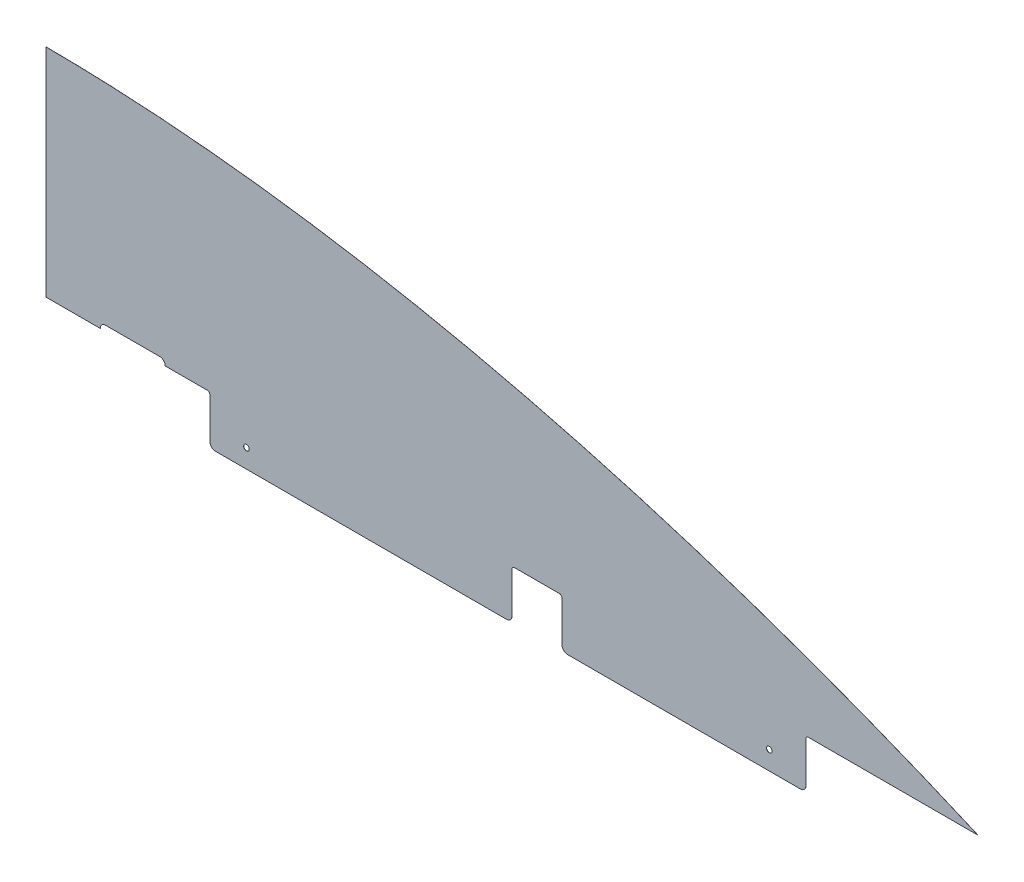
SolidWorks part; units mm, degrees
material "PC High Viscosity"
ref_plane "Front Plane" through (0, 0, 0) normal (0, 0, 1) x (1, 0, 0)
ref_plane "Top Plane" through (0, 0, 0) normal (0, 1, 0) x (1, 0, 0)
ref_plane "Right Plane" through (0, 0, 0) normal (1, 0, 0) x (0, 0, -1)
sketch "Sketch1" plane through (0, 0, 0) normal (0, 0, 1) x (1, 0, 0)
  line L0 (0, 254) -> (0, 0)
  line L1 (0, 0) -> (1092.2, 0)
  spline S0 degree 3 poles (0, 254) (376.5132, 252.2764) (770.2858, 140.4997) (1092.2, 0) knots 0 0 0 0 1 1 1 1
  dimension "D1" = 1092.2
  dimension "D2" = 254
extrude "Boss-Extrude1" add sketch "Sketch1" along normal blind 0.127
sketch "Sketch2" plane through (0, 0, 0.127) normal (0, 0, 1) x (1, 0, 0)
  line L0 (0, 30.48) -> (1020.0945, 30.48) construction
  line L1 (0, 254) -> (0, 0) construction
  line L2 (0, 0) -> (1092.2, 0) construction
  spline S0 degree 3 poles (1092.2, 0) (770.2858, 140.4997) (376.5132, 252.2764) (0, 254) knots 0 0 0 0 1 1 1 1 construction
  point P8 (63.5, 30.48)
  point P9 (977.9, 30.48)
  dimension "D1" = 30.48
  dimension "D2" = 63.5
  dimension "D3" = 914.4
hole_wizard "F (0.257) Diameter Hole1" [suppressed] positions "Sketch3" profile "Sketch4" hole size "F" standard "ANSI Inch"
sketch "Sketch3" plane through (0, 0, 6.35) normal (0, 0, 1) x (1, 0, 0)
  point P0 (63.5, 30.48)
  point P3 (977.9, 30.48)
sketch "Sketch4" plane through (63.5, 30.48, 6.35) normal (1, 0, 0) x (0, -1, 0)
  line L0 (0, 0) -> (0, 6.35)
  line L1 (0, 6.35) -> (3.2639, 6.35)
  line L2 (3.2639, 6.35) -> (3.2639, 0)
  line L5 (3.2639, 0) -> (0, 0)
  line L11 (0, -6.35) -> (0, 107.95) construction
  dimension "Thru Hole Dia." = 6.5278
  dimension "Thru Hole Depth" = 6.35
sketch "Sketch5" plane through (0, 0, 0) normal (0, 0, -1) x (-1, 0, 0)
  line L0 (0, 0) -> (-1092.2, 0) construction
  line L1 (-130.175, 0) -> (-247.65, 0)
  line L2 (-130.175, 0) -> (-130.175, -38.1)
  line L3 (-130.175, -38.1) -> (-247.65, -38.1)
  line L4 (-247.65, 0) -> (-247.65, -38.1)
  line L6 (-815.975, 0) -> (-933.45, 0)
  line L7 (-815.975, 0) -> (-815.975, -38.1)
  line L8 (-815.975, -38.1) -> (-933.45, -38.1)
  line L9 (-933.45, 0) -> (-933.45, -38.1)
  dimension "D1" = 130.175
  dimension "D2" = 568.325
  dimension "D3" = 117.475
  dimension "D4" = 38.1
extrude "Boss-Extrude2" [suppressed] add sketch "Sketch5" against normal up to surface (6.35 mm away)
fillet "Fillet1" [suppressed] radius 3.175
sketch "Sketch6" [suppressed] plane through (0, 0, 0) normal (0, 0, -1) x (-1, 0, 0)
  line L0 (-936.625, 0) -> (-127, 0) construction
  line L1 (-130.175, -6.35) -> (-933.45, -6.35) construction
  line L2 (-130.175, -34.925) -> (-130.175, -3.175) construction
  line L3 (-933.45, -3.175) -> (-933.45, -34.925) construction
  line L4 (-874.7125, -38.1) -> (-874.7125, 0) construction
  line L5 (-930.275, -38.1) -> (-819.15, -38.1) construction
  line L6 (-819.15, -38.1) -> (-244.475, -38.1) construction
  line L7 (-531.8125, -38.1) -> (-531.8125, 0) construction
  line L8 (-188.9125, -38.1) -> (-188.9125, 0) construction
  arc A0 (-933.45, -3.175) -> (-936.625, 0) centre (-936.625, -3.175) ccw construction
  circle A1 centre (-908.05, -9.7282) radius 3.3782
  circle A2 centre (-908.05, 3.3782) radius 3.3782
  circle A3 centre (-841.375, 3.3782) radius 3.3782
  circle A4 centre (-841.375, -9.7282) radius 3.3782
  circle A5 centre (-222.25, -9.7282) radius 3.3782
  circle A6 centre (-222.25, 3.3782) radius 3.3782
  circle A7 centre (-155.575, 3.3782) radius 3.3782
  circle A8 centre (-155.575, -9.7282) radius 3.3782
  dimension "D2" = 6.7564
  dimension "D1" = 6.35
  dimension "D3" = 25.4
extrude "Cut-Extrude1" [suppressed] cut sketch "Sketch6" against normal through all
sketch "Sketch7" plane through (0, 0, 0) normal (0, 0, -1) x (-1, 0, 0)
  line L0 (0, 0) -> (-1092.2, 0) construction
  line L1 (-63.5, 0) -> (-133.35, 0)
  line L3 (-69.85, 6.35) -> (-133.35, 6.35)
  line L4 (0, 0) -> (-1092.2, 0) construction
  arc A0 (-133.35, 6.35) -> (-139.7, 0) centre (-133.35, 0) ccw
  arc A1 (-69.85, 6.35) -> (-63.5, 0) centre (-69.85, 0) cw
  dimension "D1" = 6.35
  dimension "D2" = 63.5
  dimension "D3" = 63.5
extrude "Cut-Extrude2" cut sketch "Sketch7" against normal through all
sketch "Sketch8" plane through (0, 0, 0.127) normal (0, 0, 1) x (1, 0, 0)
  line L0 (139.7, 0) -> (1092.2, 0) construction
  line L1 (192.0875, 0) -> (890.5875, 0)
  line L2 (192.0875, 0) -> (192.0875, -57.15)
  line L3 (192.0875, -57.15) -> (890.5875, -57.15)
  line L4 (890.5875, 0) -> (890.5875, -57.15)
  dimension "D1" = 57.15
  dimension "D2" = 201.6125
  dimension "D3" = 52.3875
extrude "Boss-Extrude3" add sketch "Sketch8" against normal up to surface (0.127 mm away) up to face at (292.1, 20.3329, 0)
sketch "Sketch12" plane through (0, 0, 0.127) normal (0, 0, 1) x (1, 0, 0)
  line L0 (192.0875, -57.15) -> (890.5875, -57.15) construction
  line L1 (604.8375, -57.15) -> (546.1, -57.15)
  line L2 (604.8375, -57.15) -> (604.8375, 0)
  line L3 (604.8375, 0) -> (546.1, 0)
  line L4 (546.1, -57.15) -> (546.1, 0)
  line L5 (890.5875, -57.15) -> (890.5875, 0) construction
  line L6 (0, 254) -> (0, 0) construction
  line L7 (139.7, 0) -> (192.0875, 0) construction
  dimension "D1" = 285.75
  dimension "D2" = 546.1
extrude "Cut-Extrude3" cut sketch "Sketch12" against normal through all
fillet "Fillet2" radius 3.175 4 edges at (890.5875, 0, 0.0635) (192.0875, 0, 0.0635) (546.1, 0, 0.0635) (604.8375, 0, 0.0635)
fillet "Fillet3" radius 6.35 4 edges at (192.0875, -57.15, 0.0635) (890.5875, -57.15, 0.0635) (546.1, -57.15, 0.0635) (604.8375, -57.15, 0.0635)
sketch "Sketch9" plane through (0, 0, 0) normal (0, 0, -1) x (-1, 0, 0)
  line L4 (-192.0875, -50.8) -> (-192.0875, -3.175) construction
  line L5 (-884.2375, -57.15) -> (-611.1875, -57.15) construction
  line L6 (-890.5875, -3.175) -> (-890.5875, -50.8) construction
  point P0 (-234.95, -35.306)
  point P2 (-847.725, -35.306)
  dimension "D1" = 42.8625
  dimension "D2" = 21.844
  dimension "D3" = 42.8625
hole_wizard "F (0.257) Diameter Hole2" positions "Sketch10" profile "Sketch11" hole size "F" standard "ANSI Inch" end condition through all
sketch "Sketch10" plane through (0, 0, 0) normal (0, 0, -1) x (-1, 0, 0)
  point P0 (-847.725, -35.306)
  point P3 (-234.95, -35.306)
sketch "Sketch11" plane through (847.725, -35.306, 0) normal (1, 0, 0) x (0, 1, 0)
  line L0 (0, 0) -> (0, 0.127)
  line L1 (0, 0.127) -> (3.2639, 0.127)
  line L2 (3.2639, 0.127) -> (3.2639, 0)
  line L5 (3.2639, 0) -> (0, 0)
  line L11 (0, -6.35) -> (0, 107.95) construction
  dimension "Thru Hole Dia." = 6.5278
  dimension "Thru Hole Depth" = 0.127
equation "\"D3@Sketch9\"=\"D1@Sketch9\""
